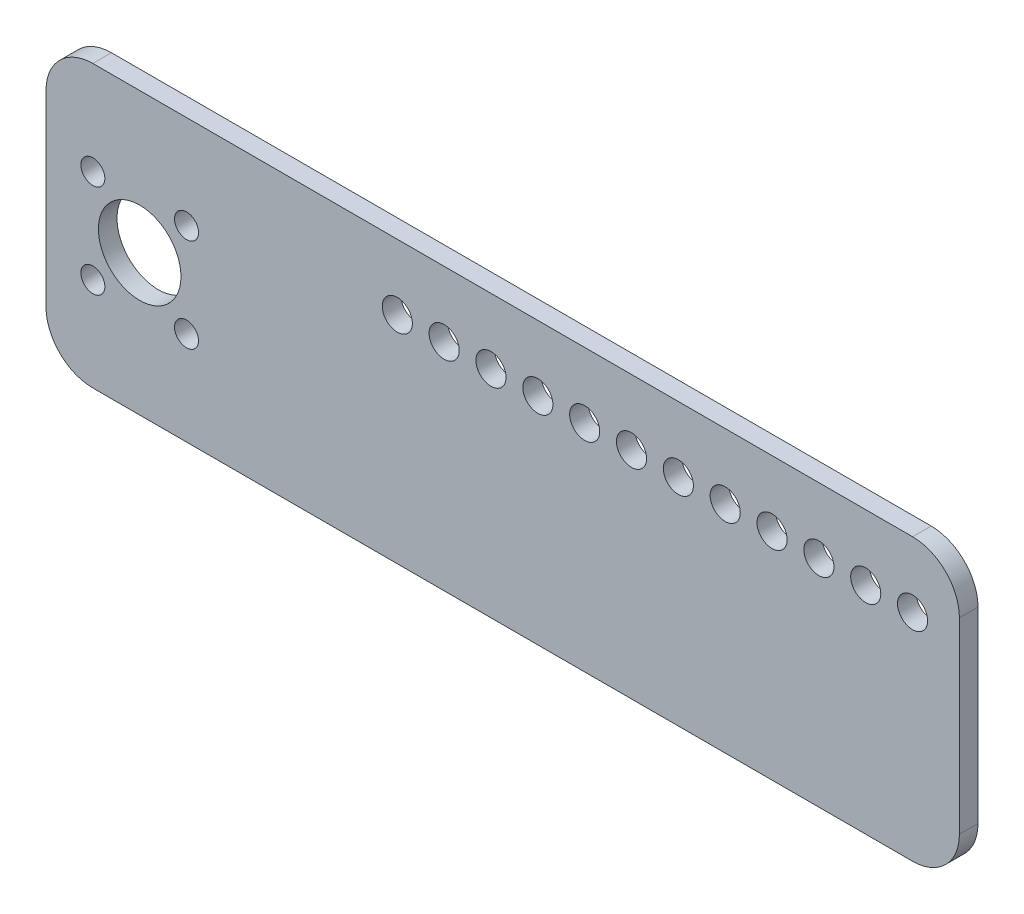
SolidWorks part; units mm, degrees
ref_plane "Front Plane" through (0, 0, 0) normal (0, 0, 1) x (1, 0, 0)
ref_plane "Top Plane" through (0, 0, 0) normal (0, 1, 0) x (1, 0, 0)
ref_plane "Right Plane" through (0, 0, 0) normal (1, 0, 0) x (0, 0, -1)
sketch "Sketch2" plane through (0, 0, 0) normal (0, 0, 1) x (1, 0, 0)
  line L0 (0, 0) -> (0, -72030.4166) construction
  line L1 (78, 24) -> (-78, 24)
  line L2 (78, 24) -> (78, -24)
  line L3 (78, -24) -> (-78, -24)
  line L4 (-78, 24) -> (-78, -24)
  line L5 (78, 24) -> (-78, -24) construction
  line L6 (78, -24) -> (-78, 24) construction
  line L7 (0, 0) -> (72030.4166, 0) construction
  line L9 (-46, 20) -> (17, 20) construction
  line L10 (-46, 20) -> (-46, -20) construction
  line L11 (-46, -20) -> (17, -20) construction
  line L12 (17, 20) -> (17, -20) construction
  line L13 (-46, 20) -> (17, -20) construction
  line L14 (-46, -20) -> (17, 20) construction
  line L15 (-70, 8) -> (-54, 8) construction
  line L16 (-70, 8) -> (-70, -8) construction
  line L17 (-70, -8) -> (-54, -8) construction
  line L18 (-54, 8) -> (-54, -8) construction
  line L19 (-70, 8) -> (-54, -8) construction
  line L20 (-70, -8) -> (-54, 8) construction
  line L21 (10.5, -16) -> (-39.5, -16) construction
  line L22 (10.5, -16) -> (10.5, 16) construction
  line L23 (10.5, 16) -> (-39.5, 16) construction
  line L24 (-39.5, -16) -> (-39.5, 16) construction
  line L25 (10.5, -16) -> (-39.5, 16) construction
  line L26 (10.5, 16) -> (-39.5, -16) construction
  line L31 (7.35, -12) -> (-36.35, -12) construction
  line L32 (7.35, -12) -> (7.35, -8) construction
  line L33 (-50, -12) -> (-74, -12) construction
  line L34 (-50, -12) -> (-50, 12) construction
  line L35 (-50, 12) -> (-74, 12) construction
  line L36 (-74, -12) -> (-74, 12) construction
  line L37 (-50, -12) -> (-74, 12) construction
  line L38 (-50, 12) -> (-74, -12) construction
  line L39 (7.35, 12) -> (-36.35, 12) construction
  line L40 (-36.35, -12) -> (-36.35, -8) construction
  line L41 (7.35, -12) -> (-36.35, 12) construction
  line L42 (7.35, 12) -> (-36.35, -12) construction
  line L44 (-4.7, 19.1) -> (47.7956, 19.1) construction
  line L45 (5.35, -10) -> (-34.35, -10) construction
  line L46 (5.35, -10) -> (5.35, 10) construction
  line L47 (5.35, 10) -> (-34.35, 10) construction
  line L48 (-34.35, -10) -> (-34.35, 10) construction
  line L49 (5.35, -10) -> (-34.35, 10)
  line L50 (5.35, 10) -> (-34.35, -10)
  line L51 (-4.7, -19.1) -> (47.7956, -19.1) construction
  line L52 (-36.35, 8) -> (-42, 8) construction
  line L53 (13, -8) -> (7.35, -8) construction
  line L54 (13, -8) -> (13, 8) construction
  line L55 (13, 8) -> (7.35, 8) construction
  line L56 (-42, -8) -> (-42, 8) construction
  line L57 (13, -8) -> (-42, 8) construction
  line L58 (13, 8) -> (-42, -8) construction
  line L59 (-36.35, -8) -> (-42, -8) construction
  line L60 (-36.35, 8) -> (-36.35, 12) construction
  line L61 (7.35, 8) -> (7.35, 12) construction
  line L64 (9.0311, 16) -> (-48518.2868, 16) construction
  line L65 (10.5, 18.05) -> (13.5, 18.05) construction
  line L66 (10.5, 13.95) -> (13.5, 13.95) construction
  line L67 (-21.5, 13.95) -> (-18.5, 13.95) construction
  line L68 (-21.5, 18.05) -> (-18.5, 18.05) construction
  line L69 (10.5, 13.95) -> (-21.5, 13.95) construction
  line L70 (-21.5, -18.05) -> (-18.5, -18.05) construction
  line L71 (-21.5, -13.95) -> (-18.5, -13.95) construction
  line L72 (10.5, -18.05) -> (13.5, -18.05) construction
  line L73 (10.5, -13.95) -> (13.5, -13.95) construction
  line L75 (72, -18) -> (-72, -18) construction
  line L76 (72, -18) -> (72, 18) construction
  line L77 (72, 18) -> (-72, 18) construction
  line L78 (-72, -18) -> (-72, 18) construction
  line L79 (72, -18) -> (-72, 18) construction
  line L80 (72, 18) -> (-72, -18) construction
  circle A0 centre (-70, 8) radius 2.05
  circle A1 centre (-54, 8) radius 2.05
  circle A2 centre (-54, -8) radius 2.05
  circle A3 centre (-70, -8) radius 2.05
  arc A6 (10.5, 18.05) -> (10.5, 13.95) centre (10.5, 16) ccw construction
  circle A7 centre (-39.5, 16) radius 2.05 construction
  circle A8 centre (-39.5, -16) radius 2.05 construction
  circle A9 centre (-4.7, 0) radius 19.1 construction
  arc A12 (-4.7, 19.1) -> (-4.7, -19.1) centre (-4.7, 0) ccw construction
  circle A13 centre (47.7956, 0) radius 19.1 construction
  arc A14 (47.7956, -19.1) -> (47.7956, 19.1) centre (47.7956, 0) ccw construction
  arc A15 (-4.7, 19.1) -> (-4.7, -19.1) centre (-4.7, 0) ccw construction
  circle A16 centre (47.7956, 0) radius 7.05 construction
  arc A18 (13.5, 13.95) -> (13.5, 18.05) centre (13.5, 16) ccw construction
  arc A19 (-18.5, 13.95) -> (-18.5, 18.05) centre (-18.5, 16) ccw construction
  arc A20 (-21.5, 18.05) -> (-21.5, 13.95) centre (-21.5, 16) ccw construction
  arc A21 (-21.5, -18.05) -> (-21.5, -13.95) centre (-21.5, -16) cw construction
  arc A22 (-18.5, -13.95) -> (-18.5, -18.05) centre (-18.5, -16) cw construction
  arc A23 (10.5, -18.05) -> (10.5, -13.95) centre (10.5, -16) cw construction
  arc A24 (13.5, -13.95) -> (13.5, -18.05) centre (13.5, -16) cw construction
  circle A25 centre (-62, 0) radius 7.05
  circle A26 centre (72, 18) radius 2.05 construction
  circle A27 centre (72, -18) radius 2.05 construction
  circle A28 centre (-72, -18) radius 2.05 construction
  circle A29 centre (-72, 18) radius 2.05 construction
  point P0 (0, 0)
  point P10 (-14.5, 0)
  point P15 (-62, 0)
  point P20 (-14.5, 0)
  point P25 (-14.5, 0)
  point P30 (-62, 0)
  point P39 (-14.5, 0)
  point P47 (-14.5, 0)
  point P52 (-14.5, 0)
  point P95 (0, 0)
  dimension "D7" = 4.1
  dimension "D14" = 38.2
  dimension "D21" = 14.1
  dimension "D1" = 156
  dimension "D2" = 48
  dimension "D3" = 63
  dimension "D4" = 40
  dimension "D5" = 50
  dimension "D6" = 32
  dimension "D8" = 16
  dimension "D9" = 16
  dimension "D10" = 24
  dimension "D11" = 24
  dimension "D12" = 43.7
  dimension "D13" = 24
  dimension "D16" = 39.7
  dimension "D17" = 20
  dimension "D18" = 10.05
  dimension "D19" = 4
  dimension "D20" = 8
  dimension "D22" = 55
  dimension "D23" = 16
  dimension "D24" = 3
  dimension "D26" = 32
  dimension "D27" = 144
  dimension "D28" = 36
  dimension "D25" = 2
extrude "Boss-Extrude2" add sketch "Sketch2" along normal blind 3.175
fillet "Fillet1" radius 8 4 edges at (78, -24, 1.5875) (78, 24, 1.5875) (-78, -24, 1.5875) (-78, 24, 1.5875)
sketch "Sketch3" plane through (0, 0, 3.175) normal (0, 0, 1) x (1, 0, 0)
  line L0 (0, 0) -> (0, 50000) construction
  line L1 (0, 0) -> (50000, 0) construction
  line L2 (0, 12.825) -> (50000, 12.825) construction
  line L3 (70, 24) -> (-70, 24) construction
  line L4 (-18, 6.1223) -> (-18, 2.2514) construction
  line L5 (78, 16) -> (78, -16) construction
  circle A0 centre (70, 12.825) radius 2.5717
  circle A1 centre (62, 12.825) radius 2.5717
  circle A2 centre (54, 12.825) radius 2.5717
  circle A3 centre (46, 12.825) radius 2.5717
  circle A4 centre (38, 12.825) radius 2.5717
  circle A5 centre (30, 12.825) radius 2.5717
  circle A6 centre (22, 12.825) radius 2.5717
  circle A7 centre (14, 12.825) radius 2.5717
  circle A8 centre (6, 12.825) radius 2.5717
  circle A9 centre (-2, 12.825) radius 2.5717
  circle A10 centre (-10, 12.825) radius 2.5717
  circle A11 centre (-18, 12.825) radius 2.5717
  dimension "D1" = 11.175
  dimension "D2" = 96
  dimension "D3" = 8
  dimension "D4" = 12
extrude "Cut-Extrude1" cut sketch "Sketch3" against normal blind 10
equation "\"w\"= 156mm"
equation "\"h\"= 48mm"
equation "\"servoheight\"= 40mm"
equation "\"servowidth\"= 63mm"
equation "\"servowidthholes\"= 50mm"
equation "\"servoheightholes\"= 32mm"
equation "\"sh\"= 4.1mm"
equation "\"clampHoleSquare\"= 16mm"
equation "\"clampSquare\"= 24mm"
equation "\"D1@Sketch2\"=\"w\""
equation "\"D2@Sketch2\"=\"h\""
equation "\"D3@Sketch2\"=\"servowidth\""
equation "\"D4@Sketch2\"=\"servoheight\""
equation "\"D5@Sketch2\"=\"servowidthholes\""
equation "\"D6@Sketch2\"=\"servoheightholes\""
equation "\"D8@Sketch2\"=\"clampHoleSquare\""
equation "\"D9@Sketch2\"=\"clampHoleSquare\""
equation "\"D10@Sketch2\"=\"clampSquare\""
equation "\"D11@Sketch2\"=\"clampSquare\""
equation "\"D7@Sketch2\"=\"sh\""
equation "\"servoh\"= 20mm"
equation "\"servow\"= 39.7mm"
equation "\"D12@Sketch2\"=\"servow\"+4"
equation "\"D13@Sketch2\"=\"servoh\" +4"
equation "\"pitchDiameter\"= 38.2mm"
equation "\"D14@Sketch2\"=\"pitchDiameter\""
equation "\"D16@Sketch2\"=\"servow\""
equation "\"D17@Sketch2\"=\"servoh\""
equation "\"D18@Sketch2\"=10.05mm"
equation "\"pathLength\"= 225mm"
equation "\"D15@Sketch2\"=\"pathLength\""
equation "\"bearingOD\"= 14.1mm"
equation "\"D21@Sketch2\"=\"bearingOD\""
equation "\"thick\"= 3.175mm"
equation "\"D1@Boss-Extrude2\"=\"thick\""
equation "\"D27@Sketch2\"=\"w\"-12"
equation "\"D28@Sketch2\"=\"h\"-12"
equation "\"D1@Sketch3\"=\"thick\"+8"
